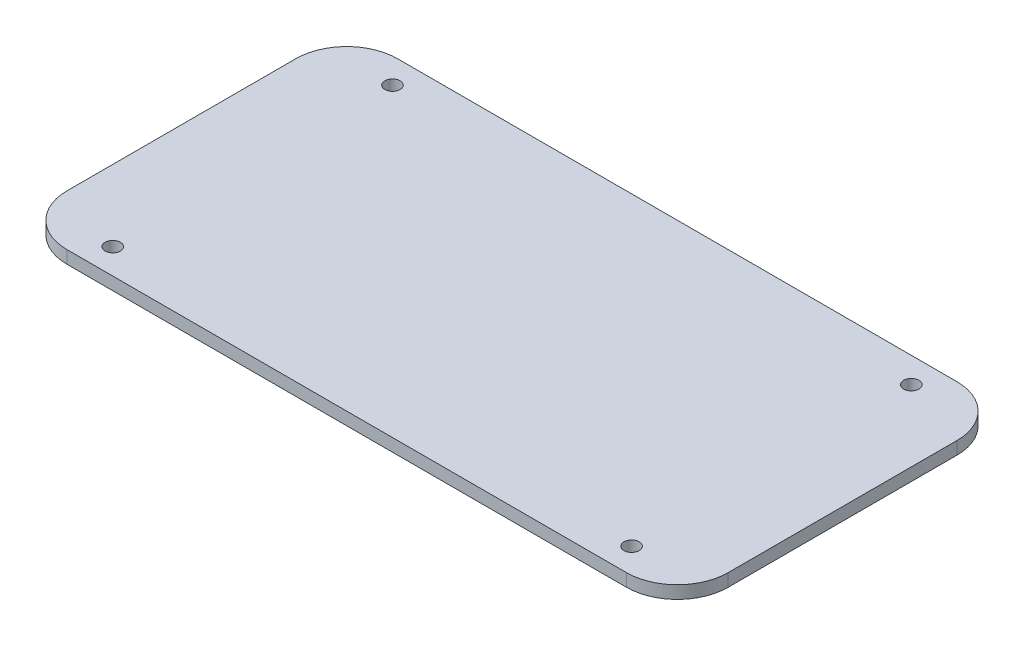
SolidWorks part; units mm, degrees
ref_plane "Front Plane" through (0, 0, 0) normal (0, 0, 1) x (1, 0, 0)
ref_plane "Top Plane" through (0, 0, 0) normal (0, 1, 0) x (1, 0, 0)
ref_plane "Right Plane" through (0, 0, 0) normal (1, 0, 0) x (0, 0, -1)
sketch "Sketch1" plane through (0, 0, 0) normal (0, 1, 0) x (1, 0, 0)
  line L1 (10, 0) -> (120, 0)
  line L2 (0, 10) -> (0, 55)
  line L3 (10, 65) -> (120, 65)
  line L4 (130, 10) -> (130, 55)
  arc A0 (10, 65) -> (0, 55) centre (10, 55) ccw
  arc A1 (0, 10) -> (10, 0) centre (10, 10) ccw
  arc A2 (130, 10) -> (120, 0) centre (120, 10) cw
  arc A3 (120, 65) -> (130, 55) centre (120, 55) cw
  point P7 (0, 65)
  point P10 (0, 0)
  point P13 (130, 0)
  dimension "D3" = 10
  dimension "D4" = 10
  dimension "D5" = 10
  dimension "D6" = 10
  dimension "D1" = 130
  dimension "D2" = 65
extrude "Boss-Extrude1" add sketch "Sketch1" along normal blind 2.5
sketch "Sketch2" plane through (0, 2.5, 0) normal (0, 1, 0) x (1, 0, 0)
  line L0 (0, 55) -> (0, 10) construction
  line L1 (10, 0) -> (120, 0) construction
  line L2 (120, 65) -> (10, 65) construction
  line L3 (65, 55) -> (65, 0) construction
  circle A0 centre (14, 5) radius 1.5
  circle A1 centre (14, 60) radius 1.5
  circle A2 centre (116, 5) radius 1.5
  circle A3 centre (116, 60) radius 1.5
  dimension "D1" = 3
  dimension "D4" = 3
  dimension "D2" = 14
  dimension "D3" = 5
  dimension "D5" = 5
extrude "Cut-Extrude1" cut sketch "Sketch2" against normal through all
